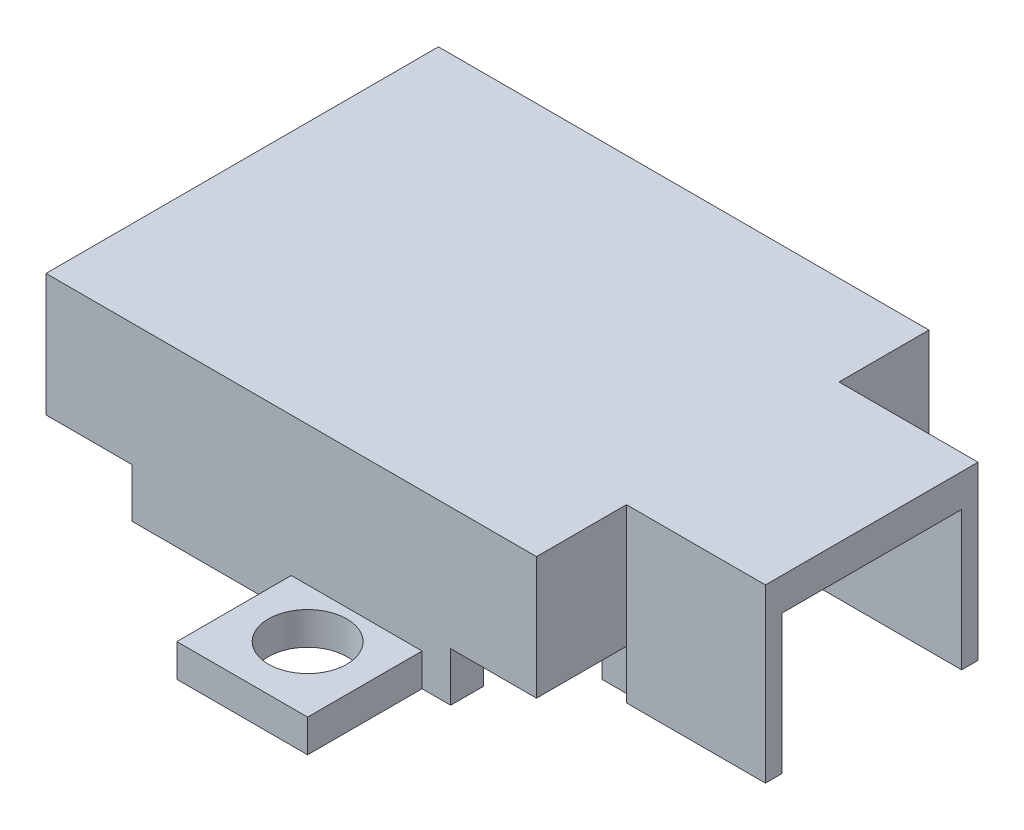
SolidWorks part; units mm, degrees
ref_plane "前视基准面" through (0, 0, 0) normal (0, 0, 1) x (1, 0, 0)
ref_plane "上视基准面" through (0, 0, 0) normal (0, 1, 0) x (1, 0, 0)
ref_plane "右视基准面" through (0, 0, 0) normal (1, 0, 0) x (0, 0, -1)
other "Configuration Table"
sketch "草图1" plane through (0, 0, 0) normal (0, 1, 0) x (1, 0, 0)
  line L1 (-15, -12) -> (15, -12)
  line L2 (-15, -12) -> (-15, 12)
  line L3 (-15, 12) -> (15, 12)
  line L4 (15, -12) -> (15, 12)
  line L5 (-15, -12) -> (15, 12) construction
  line L6 (-15, 12) -> (15, -12) construction
  point P0 (0, 0)
  dimension "D1" = 30
  dimension "D2" = 24
extrude "凸台-拉伸1" add sketch "草图1" along normal blind 2
sketch "草图2" plane through (0, 0, 0) normal (0, -1, 0) x (1, 0, 0)
  line L0 (0, 0) -> (50000, 0) construction
  line L1 (-15, 12) -> (-9.75, 12)
  line L2 (-15, 12) -> (-15, 6)
  line L3 (-15, 6) -> (-9.75, 6)
  line L4 (-9.75, 12) -> (-9.75, 6)
  line L5 (0, 0) -> (0, 50000) construction
  line L6 (9.75, 12) -> (9.75, 6)
  line L7 (15, 6) -> (9.75, 6)
  line L8 (15, 12) -> (15, 6)
  line L9 (15, 12) -> (9.75, 12)
  line L10 (15, -12) -> (9.75, -12)
  line L11 (15, -12) -> (15, -6)
  line L12 (15, -6) -> (9.75, -6)
  line L13 (9.75, -12) -> (9.75, -6)
  line L14 (-9.75, -12) -> (-9.75, -6)
  line L15 (-15, -6) -> (-9.75, -6)
  line L16 (-15, -12) -> (-15, -6)
  line L17 (-15, -12) -> (-9.75, -12)
  line L18 (15, 12) -> (15, -12) construction
  line L19 (-9.75, 12) -> (9.75, 12)
  line L20 (-9.75, 12) -> (-9.75, 10)
  line L21 (-9.75, 10) -> (9.75, 10)
  line L22 (9.75, 12) -> (9.75, 10)
  line L23 (-9.75, -12) -> (9.75, -12)
  line L24 (-9.75, -12) -> (-9.75, -10)
  line L25 (-9.75, -10) -> (9.75, -10)
  line L26 (9.75, -12) -> (9.75, -10)
  line L27 (13, 6) -> (15, 6)
  line L28 (13, 6) -> (13, 5.5)
  line L29 (13, 5.5) -> (15, 5.5)
  line L30 (15, 6) -> (15, 5.5)
  line L32 (15, -6) -> (13, -6)
  line L33 (15, -6) -> (15, -5.5)
  line L34 (15, -5.5) -> (13, -5.5)
  line L35 (13, -6) -> (13, -5.5)
  line L36 (-15, 6) -> (-13, 6)
  line L37 (-15, 6) -> (-15, -6)
  line L38 (-15, -6) -> (-13, -6)
  line L39 (-13, 6) -> (-13, -6)
  line M30 (15, -12) -> (15, 12)
  line M31 (15, 12) -> (-15, 12)
  line M32 (-15, 12) -> (-15, -12)
  line M33 (-15, -12) -> (15, -12)
  dimension "D1" = 5.25
  dimension "D2" = 6
  dimension "D3" = 2
  dimension "D4" = 2
  dimension "D5" = 2
  dimension "D6" = 11
  dimension "D7" = 2
extrude "凸台-拉伸2" add sketch "草图2" along normal blind 5.5 contours L4 L3 M31 M32 | L4 L21 L6 M31 | L7 L6 M30 M31 | L28 L29 L7 M30 | L35 L12 L34 M30 | L13 L12 M33 M30 | L25 L14 L13 M33 | L15 L14 M32 M33 | L39 L3 L15 M32
sketch "草图3" plane through (0, -5.5, 0) normal (0, -1, 0) x (1, 0, 0)
  line L0 (15, 12) -> (-15, 12) construction
  line L1 (-9.75, 10) -> (9.75, 10)
  line L2 (-9.75, 10) -> (-9.75, 12)
  line L3 (-9.75, 12) -> (9.75, 12)
  line L4 (9.75, 10) -> (9.75, 12)
  line L5 (-15, -12) -> (15, -12) construction
  line L6 (-9.75, -10) -> (9.75, -10)
  line L7 (-9.75, -10) -> (-9.75, -12)
  line L8 (-9.75, -12) -> (9.75, -12)
  line L9 (9.75, -10) -> (9.75, -12)
  line L10 (9.75, 10) -> (9.75, 6) construction
  line L11 (13, -6) -> (15, -6)
  line L12 (13, -6) -> (13, -5.5)
  line L13 (13, -5.5) -> (15, -5.5)
  line L14 (15, -6) -> (15, -5.5)
  line L15 (13, 6) -> (15, 6)
  line L16 (13, 6) -> (13, 5.5)
  line L17 (13, 5.5) -> (15, 5.5)
  line L18 (15, 6) -> (15, 5.5)
extrude "凸台-拉伸3" add sketch "草图3" along normal blind 3
sketch "草图4" plane through (0, 2, 0) normal (0, 1, 0) x (1, 0, 0)
  line L0 (15, -12) -> (15, 12) construction
  line L1 (15, 6.5) -> (23.5, 6.5)
  line L2 (15, 6.5) -> (15, -6.5)
  line L3 (15, -6.5) -> (23.5, -6.5)
  line L4 (23.5, 6.5) -> (23.5, -6.5)
  line L5 (0, 0) -> (50000, 0) construction
  dimension "D1" = 8.5
  dimension "D2" = 13
extrude "凸台-拉伸4" add sketch "草图4" against normal blind 2
sketch "草图5" plane through (0, 0, 0) normal (0, -1, 0) x (1, 0, 0)
  line L0 (15, 5.5) -> (15, 6) construction
  line L1 (23.5, 6.5) -> (15, 6.5)
  line L2 (23.5, 6.5) -> (23.5, 5.5)
  line L3 (23.5, 5.5) -> (15, 5.5)
  line L4 (15, 6.5) -> (15, 5.5)
  line L5 (15, -6.5) -> (15, -5.5) construction
  line L6 (23.5, -6.5) -> (15, -6.5)
  line L7 (23.5, -6.5) -> (23.5, -5.5)
  line L8 (23.5, -5.5) -> (15, -5.5)
  line L9 (15, -6.5) -> (15, -5.5)
  dimension "D1" = 1
extrude "凸台-拉伸5" add sketch "草图5" along normal up to surface (8.5 mm away) up to face at (14, -8.5, -5.75)
sketch "草图6" plane through (0, -8.5, 0) normal (0, -1, 0) x (1, 0, 0)
  line L0 (9.75, 12) -> (-9.75, 12) construction
  line L1 (0, 12) -> (8, 12)
  line L2 (0, 12) -> (0, 19)
  line L3 (0, 19) -> (8, 19)
  line L4 (8, 12) -> (8, 19)
  line L6 (-15, 12) -> (-15, -12) construction
  line L7 (0, 0) -> (50000, 0) construction
  line L8 (0, -19) -> (8, -12) construction
  line L9 (8, -12) -> (8, -19)
  line L10 (0, -19) -> (8, -19)
  line L11 (0, -12) -> (0, -19)
  line L12 (0, -12) -> (8, -12)
  circle A0 centre (4, 15) radius 2.4
  circle A1 centre (4, -15) radius 2.4
  point P20 (4, 19)
  dimension "D2" = 4.8
  dimension "D5" = 30
  dimension "D1" = 7
  dimension "D3" = 19
  dimension "D4" = 8
extrude "凸台-拉伸6" add sketch "草图6" against normal blind 2 contours L9 L10 L11 L12 | L2 L1 L4 L3 | A1 | A0
sketch "草图7" plane through (0, -5.5, 0) normal (0, -1, 0) x (1, 0, 0)
  line L0 (-9.75, 10) -> (-9.75, 6) construction
  line L1 (-13, 6) -> (-9.75, 6)
  line L2 (-13, 6) -> (-13, 9)
  line L3 (-13, 9) -> (-9.75, 9)
  line L4 (-9.75, 6) -> (-9.75, 9)
  dimension "D1" = 3
extrude "切除-拉伸1" cut sketch "草图7" against normal up to surface (5.5 mm away) up to face at (4.5625, 0, 0)
